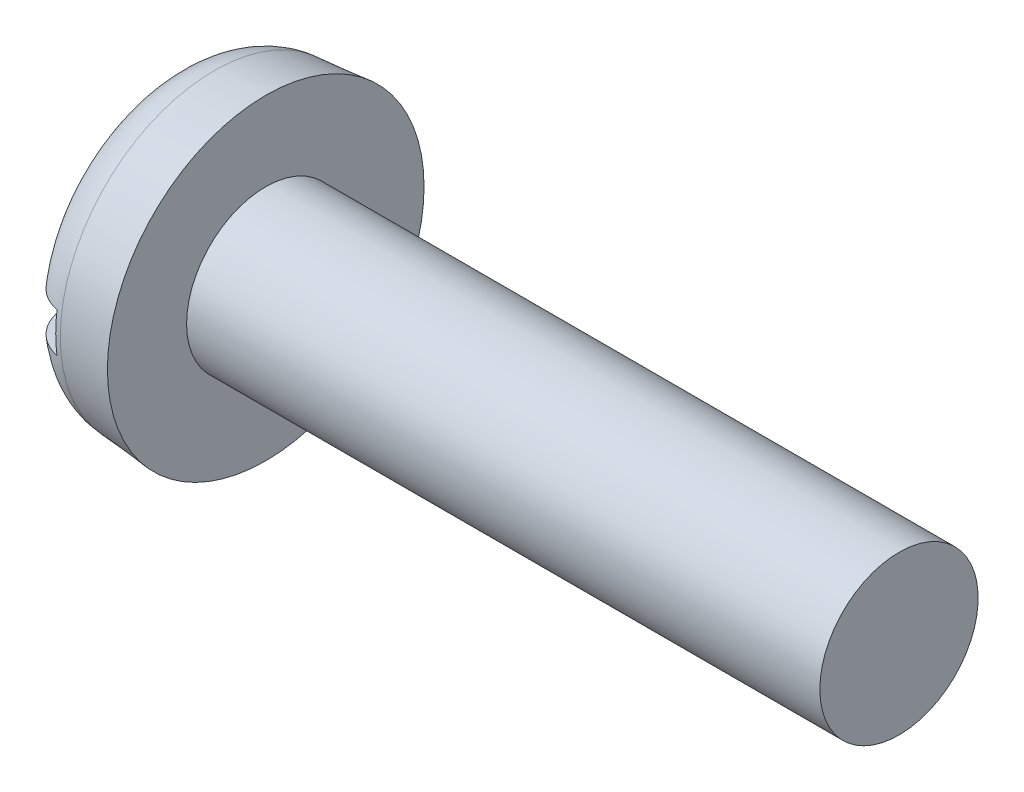
SolidWorks part; units mm, degrees
ref_plane "Plane1" through (0, 0, 0) normal (0, 0, 1) x (1, 0, 0)
ref_plane "Plane2" through (0, 0, 0) normal (0, 1, 0) x (1, 0, 0)
ref_plane "Plane3" through (0, 0, 0) normal (1, 0, 0) x (0, 0, -1)
sketch "BodySke" plane through (0, 0, 0) normal (0, 0, 1) x (1, 0, 0)
  line L0 (6, 5) -> (6, 10)
  line L1 (0, 0) -> (0, 9.4751)
  line L2 (-25.4, 0) -> (127, 0) construction
  line L3 (46, 0) -> (0, 0)
  line L4 (6, 5) -> (46, 5)
  line L5 (46, 5) -> (46, 0)
  line L6 (0, 9.4751) -> (6, 10)
  line L9 (7.5, 6.5875) -> (7.5, -2.9375) construction
  line L10 (6, 6.35) -> (6, -3.175) construction
  dimension "Length" = 40
  dimension "Head_ht" = 6
  dimension "Advance" = 1.5
  dimension "Thread_nom" = 40
  dimension "Head_dia" = 20
  dimension "Head_side_angle" = 5
  dimension "Diameter" = 10
revolve "Base-Revolve" add sketch "BodySke"
cosmetic thread "ThreadCosmetic" [suppressed]
fillet "Fillet1" [suppressed] radius 0.4
fillet "Fillet2" radius 3 1 edges at (0, 0, 9.4751)
sketch "Sketch2" plane through (0, 0, 0) normal (1, 0, 0) x (0, 0, -1)
  line L0 (10, -1.25) -> (-10, -1.25)
  line L1 (10, -1.25) -> (10, 1.25)
  line L2 (-10, 1.25) -> (10, 1.25)
  line L3 (-10, 1.25) -> (-10, -1.25)
  dimension "D1" = 20
  dimension "Slot_width" = 2.5
  dimension "D2" = 10
  dimension "D3" = 1.25
extrude "Slot" cut sketch "Sketch2" along normal blind 2.4
sketch "ThdSchSke" plane through (0, 0, 0) normal (0, 0, 1) x (1, 0, 0)
  line L0 (9, -4.1885) -> (8.4318, -5)
  line L1 (9, -4.1885) -> (9.5682, -5)
  line L2 (9.5682, -5) -> (9.5682, -6.25)
  line L3 (-3.175, 0) -> (5.1513, 0) construction
  line L5 (9.5682, -6.25) -> (8.4318, -6.25)
  line L6 (8.4318, -6.25) -> (8.4318, -5)
  dimension "Diameter" = 10
  dimension "SideAngle" = 55
  dimension "VeeAngle" = 70
  dimension "Thread_minor" = 8.377
  dimension "Overcut" = 12.5
  dimension "Start" = 9
revolve "ThreadSchematic" [suppressed] cut sketch "ThdSchSke" angle 360 about L3
pattern_linear "ThdSchPat" [suppressed]
equation "\"D1@Sketch2\" = \"Head_dia@BodySke\""
equation "\"D2@Sketch2\" = \"D1@Sketch2\" / 2"
equation "\"D3@Sketch2\" = \"Slot_width@Sketch2\" / 2"
equation "\"Thread_length@ThreadCosmetic\" = ((sgn( (\"Length@BodySke\" - \"Advance@BodySke\" * 2.0 ) - \"Thread_nom@BodySke\" )-1)*( (\"Length@BodySke\" - \"Advance@BodySke\"  * 2.0) - \"Thread_nom@BodySke\" ))/-2+ \"Thread_nom@BodySke\""
equation "\"Thread_minor@ThdSchSke\" = \"Thread_minor@ThreadCosmetic\""
equation "\"Diameter@ThdSchSke\" = \"Diameter@BodySke\""
equation "\"Overcut@ThdSchSke\" = \"Diameter@BodySke\" * 1.25"
equation "\"Start@ThdSchSke\" = \"Head_ht@BodySke\" + \"Length@BodySke\" - \"Thread_length@ThreadCosmetic\"  '---Non-countersunk---"
equation "\"Num_threads@ThdSchPat\" = int( \"Thread_length@ThreadCosmetic\" / \"Advance@BodySke\" + 0.999 )  + 1"
equation "\"Advance@ThdSchPat\" = \"Thread_length@ThreadCosmetic\" /  (\"Num_threads@ThdSchPat\" - 1) 'relax it"
